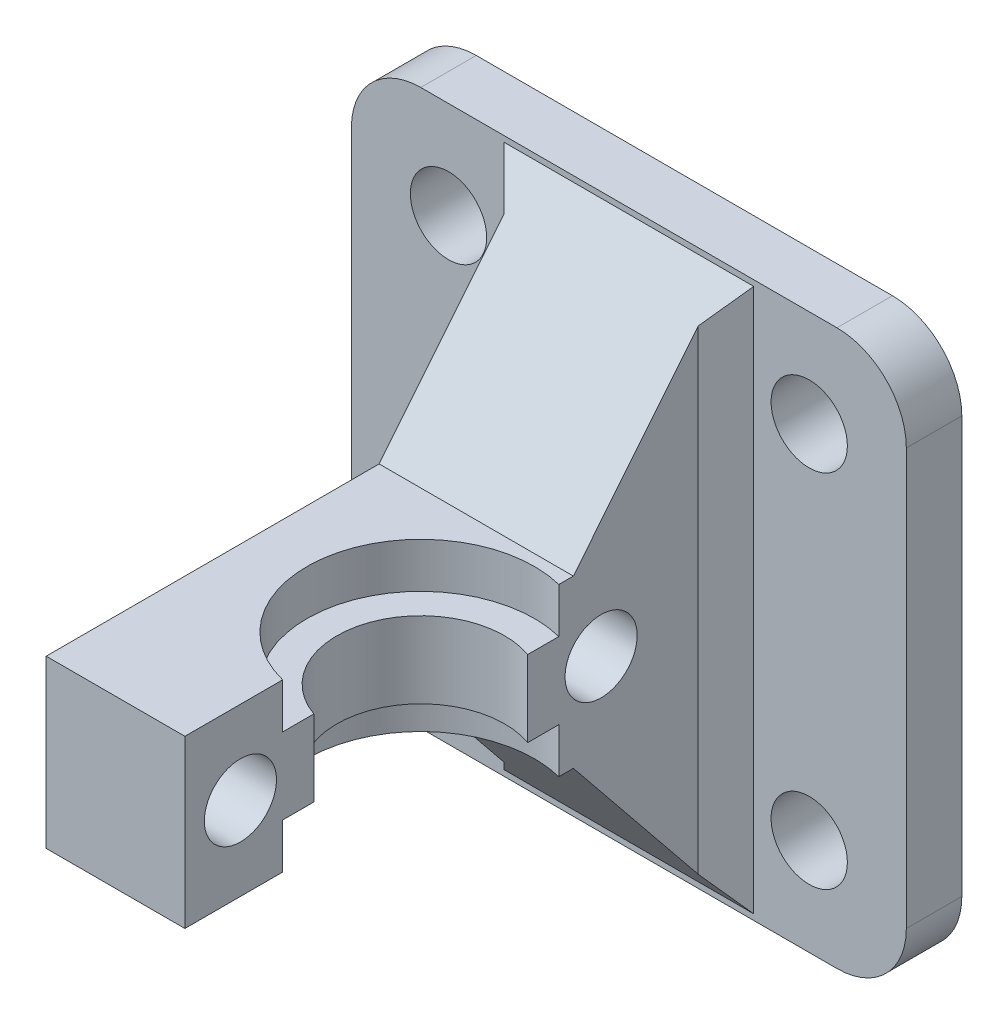
SolidWorks part; units mm, degrees
ref_plane "Front Plane" through (0, 0, 0) normal (0, 0, 1) x (1, 0, 0)
ref_plane "Top Plane" through (0, 0, 0) normal (0, 1, 0) x (1, 0, 0)
ref_plane "Right Plane" through (0, 0, 0) normal (1, 0, 0) x (0, 0, -1)
sketch "Sketch1" plane through (0, 0, 0) normal (0, 0, 1) x (1, 0, 0)
  line L1 (-20, 20) -> (20, 20)
  line L2 (-20, 20) -> (-20, -20)
  line L3 (-20, -20) -> (20, -20)
  line L4 (20, 20) -> (20, -20)
  line L5 (-20, 20) -> (20, -20) construction
  line L6 (-20, -20) -> (20, 20) construction
  point P0 (0, 0)
  dimension "D1" = 40
  dimension "D2" = 40
extrude "Boss-Extrude1" add sketch "Sketch1" along normal blind 4
sketch "Sketch2" plane through (0, 0, 0) normal (0, 0, 1) x (1, 0, 0)
  line L0 (0, 15.4248) -> (0, -21.5401) construction
  line L1 (0, -2.2) -> (0, 2.2) construction
  line L2 (-18.8374, 0) -> (26.7545, 0) construction
  line L3 (2.2, 0) -> (-2.2, 0) construction
  circle A0 centre (-13, 13) radius 2.75
  circle A1 centre (13, 13) radius 2.75
  circle A2 centre (13, -13) radius 2.75
  circle A3 centre (-13, -13) radius 2.75
  dimension "D3" = 5.5
  dimension "D1" = 13
  dimension "D2" = 13
extrude "Cut-Extrude1" cut sketch "Sketch2" along normal up to next
sketch "Sketch3" plane through (0, 0, 0) normal (0, 1, 0) x (1, 0, 0)
  line L0 (-7, -4) -> (-7, -39)
  line L1 (20, -4) -> (-20, -4) construction
  line L2 (-7, -39) -> (3, -39)
  line L3 (0, -19.8) -> (0, 19.8) construction
  line L5 (-7, -4) -> (7, -4)
  line L7 (3, -39) -> (3, -31.9524)
  line L8 (7, -16.0476) -> (7, -4)
  arc A0 (7, -16.0476) -> (3, -31.9524) centre (5, -24) ccw
  dimension "D1" = 8.2
  dimension "D2" = 2
  dimension "D3" = 10
  dimension "D4" = 35
  dimension "D5" = 14
  dimension "D6" = 15
  dimension "D7" = 7
extrude "Boss-Extrude2" add sketch "Sketch3" along normal mid plane 12
chamfer "Chamfer1" distance 11 angle 51 2 edges at (0, -6, 4) (0, 6, 4)
sketch "Sketch4" plane through (0, 0, 0) normal (1, 0, 0) x (0, 0, -1)
  line L0 (21.45, 0) -> (-21.45, 0) construction
  line L1 (-4, 19.5839) -> (-4, -19.5839) construction
  circle A0 centre (-13, 0) radius 2.6
  circle A1 centre (-35, 0) radius 2.6
  dimension "D1" = 5.2
  dimension "D2" = 5.2
  dimension "D3" = 9
  dimension "D4" = 31
extrude "Cut-Extrude2" cut sketch "Sketch4" against normal mid plane 14
sketch "Sketch5" plane through (0, 0, 0) normal (0, 1, 0) x (1, 0, 0)
  line L0 (7, -15.7386) -> (7, -18.2901)
  line L1 (3, -29.7099) -> (3, -32.2614)
  line L2 (0, -21.45) -> (0, 21.45) construction
  arc A0 (7, -18.2901) -> (3, -29.7099) centre (5, -24) ccw
  arc A1 (7, -15.7386) -> (3, -32.2614) centre (5, -24) ccw
  dimension "D1" = 12.1
  dimension "D2" = 17
  dimension "D3" = 7
  dimension "D4" = 3
extrude "Boss-Extrude3" add sketch "Sketch5" along normal mid plane 5.5
chamfer "Chamfer2" distance 2 angle 45 2 edges at (7, 0, 4) (-7, 0, 4)
fillet "Fillet1" radius 5 4 edges at (-20, -20, 2) (20, -20, 2) (20, 20, 2) (-20, 20, 2)
